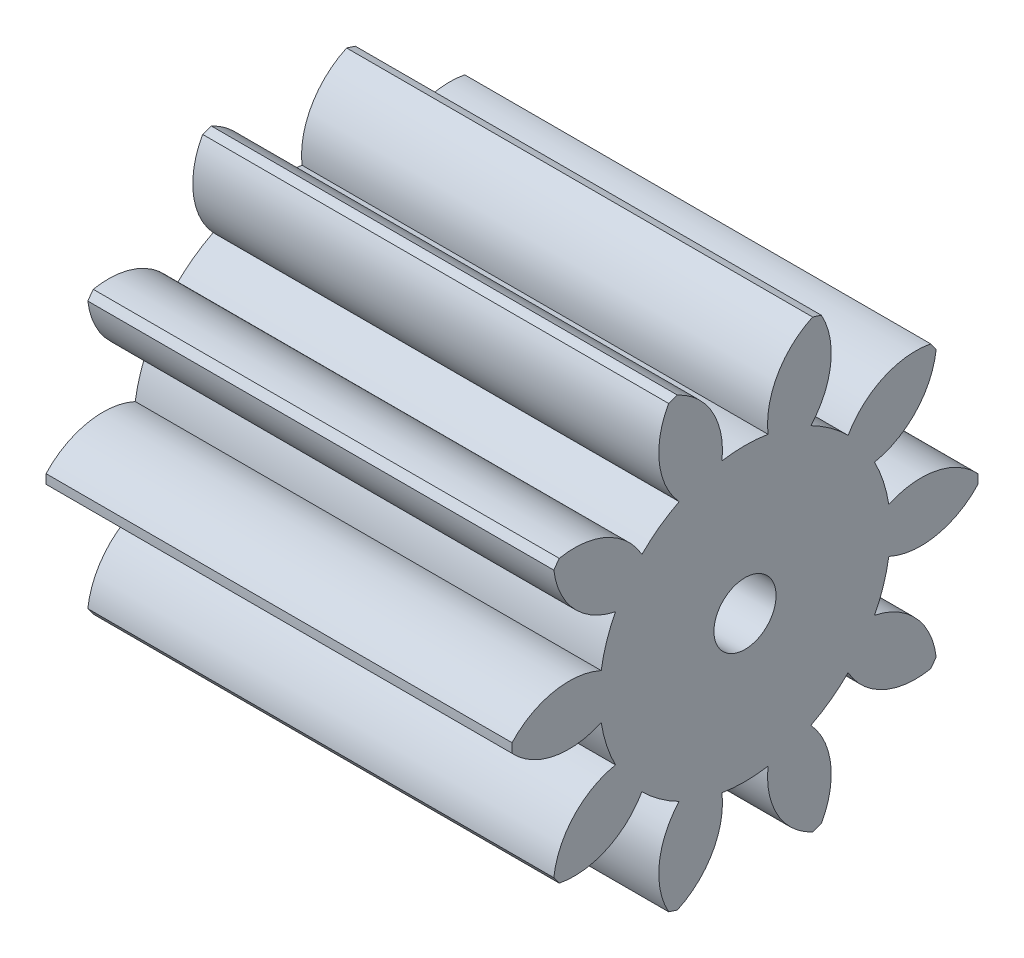
SolidWorks part; units mm, degrees
ref_plane "Plane1" through (0, 0, 0) normal (0, 0, 1) x (1, 0, 0)
ref_plane "Plane2" through (0, 0, 0) normal (0, 1, 0) x (1, 0, 0)
ref_plane "Plane3" through (0, 0, 0) normal (1, 0, 0) x (0, 0, -1)
other "Configuration Table"
sketch "HoldingSke" plane through (0, 0, 0) normal (0, 1, 0) x (1, 0, 0)
  line L0 (0, 0) -> (1.9696, -0.3473)
  line L1 (-15, 0) -> (100, 0) construction
  line L2 (0, 0) -> (-2.1039, 2.3779)
  line L3 (0, 0) -> (-11.863, 4.5341)
  line L4 (0, 0) -> (8.5048, 1.4996)
  line L5 (0, 0) -> (-46.8476, -17.4728)
  line L6 (0, 0) -> (-4.9738, -3.3558)
  line L7 (-2.1039, 2.3779) -> (8.6586, 51.2059)
  line L8 (-76.2, 54.61) -> (-76.1, 54.61)
  line L9 (-71.009, 38.7566) -> (-53.1078, 45.2721)
  line L10 (-76.2, 71.12) -> (104.1128, 71.12)
  line L11 (0, 0) -> (-6, 0)
  line L12 (-76.2, 101.6) -> (-76.181, 101.6)
  line L13 (24.9733, 27.94) -> (52.9518, 28.4284)
  line L14 (24.9733, 27.94) -> (24.9743, 27.94)
  line L15 (24.9733, 27.94) -> (100.4006, 29.5858)
  line L16 (-63.627, -0.5) -> (-12.827, -0.5)
  circle A0 centre (0, 0) radius 0.4
  circle A1 centre (0, 0) radius 1.874
  circle A2 centre (0, 0) radius 37.5
  circle A3 centre (0, 0) radius 0.4
  dimension "MHD" = 3.748
  dimension "Hub_dia" = 75
  dimension "Bore" = 0.8
  dimension "MBD" = 0.8
  dimension "Num_teeth" = 10
  dimension "Pitch" = 2
  dimension "Overall_len" = 50
  dimension "Show_teeth" = 10
  dimension "Thickness" = 6
  dimension "OAL" = 50.0001
  dimension "T_dim" = 0.1
  dimension "Ap" = 20
  dimension "H" = 19.05
  dimension "Pitch_radius" = 180.3128
  dimension "Width" = 6
  dimension "Backlash" = 0.019
  dimension "Addendum_fac" = 1
  dimension "Dedendum_fac" = 1.25
  dimension "Clearance_fac" = 0.25
  dimension "Dedendum_add" = 0.001
  dimension "Module" = 0.5
sketch "BasProSke" plane through (0, 0, 0) normal (0, 1, 0) x (1, 0, 0)
  line L0 (-10, 0) -> (60, 0) construction
  line L1 (0, 0) -> (0, 3)
  line L2 (0, 0) -> (6, 0)
  line L3 (6, 0) -> (6, 3)
  line L4 (6, 3) -> (0, 3)
  dimension "Thickness" = 6
  dimension "Diameter" = 6
revolve "Base-Revolve" add sketch "BasProSke" angle 360 about L0
sketch "TooCutSke" plane through (0, 0, 0) normal (1, 0, 0) x (0, 0, -1)
  line L1 (0, 0) -> (0, 107) construction
  line L2 (0, 0) -> (-0.4243, 2.4637) construction
  line L3 (0, 0) -> (-1.5292, 4.7063) construction
  line L4 (-0.4243, 2.4637) -> (-0.7646, 2.3532) construction
  arc A0 (0.2964, 1.8504) -> (-0.2964, 1.8504) centre (0, 0) ccw
  arc A1 (0.9059, 2.8866) -> (-0.9059, 2.8866) centre (0, 0) ccw
  circle A2 centre (0, 0) radius 2.5 construction
  circle A3 centre (0, 0) radius 2.3492 construction
  arc A4 (-0.2964, 1.8504) -> (-0.9059, 2.8866) centre (-1.2901, 1.9633) ccw
  arc A5 (0.9059, 2.8866) -> (0.2964, 1.8504) centre (1.2901, 1.9633) ccw
  dimension "Root_dia" = 3.748
  dimension "Overcut_dia" = 6.0508
  dimension "Pitch_dia" = 5
  dimension "Base_dia" = 4.6985
  dimension "Flank_rad" = 1
  dimension "Half_ang" = 18
  dimension "Half_CT" = 0.3578
extrude "ToothCut" cut sketch "TooCutSke" along normal through all
fillet "Breaks" [suppressed] radius 0.01
fillet "RootFillets" [suppressed] radius 0.126
pattern_circular "TeethCuts" count 10 every 36 about axis through (-10, 0, 0) along (1, 0, 0) of "ToothCut", "RootFillets", "Breaks"
sketch "HubNeaOneSke" plane through (0, 0, 0) normal (-1, 0, 0) x (0, 0, 1)
  circle A0 centre (0, 0) radius 1.874
  dimension "Diameter" = 3.748
extrude "HubNearOne" [suppressed] add sketch "HubNeaOneSke" along normal blind 44.0001
sketch "HubNeaBotSke" plane through (0, 0, 0) normal (-1, 0, 0) x (0, 0, 1)
  circle A0 centre (0, 0) radius 1.874
  dimension "Diameter" = 3.748
extrude "HubNearBoth" [suppressed] add sketch "HubNeaBotSke" along normal blind 22
ref_plane "FarPln" through (6, 0, 0) normal (1, 0, 0) x (0, 0, -1)
sketch "HubFarSke" plane through (6, 0, 0) normal (1, 0, 0) x (0, 0, -1)
  circle A0 centre (0, 0) radius 1.874
  dimension "Diameter" = 3.748
extrude "HubFar" [suppressed] add sketch "HubFarSke" along normal blind 22
sketch "BorSke" plane through (0, 0, 0) normal (1, 0, 0) x (0, 0, -1)
  circle A0 centre (0, 0) radius 0.4
  dimension "Diameter" = 0.8
extrude "Bore" cut sketch "BorSke" along normal mid plane 100.0001
sketch "KeySke" plane through (0, 0, 0) normal (1, 0, 0) x (0, 0, -1)
  line L0 (-0.05, 0) -> (-0.05, 0.5)
  line L1 (-0.05, 0.5) -> (0.05, 0.5)
  line L2 (0.05, 0.5) -> (0.05, 0)
  line L3 (0, 0) -> (0, 34) construction
  line L4 (-0.05, 0) -> (0.05, 0)
  dimension "Offset" = 0.5
  dimension "Width" = 0.1
extrude "Keyway" [suppressed] cut sketch "KeySke" along normal mid plane 100.0001
pattern_circular "Keyway2" [suppressed] count 2 every 90 about axis through (-10, 0, 0) along (1, 0, 0)
equation "' \"Module@HoldingSke\" = 6.35"
equation "' \"Num_teeth@HoldingSke\" = 12"
equation "' \"Ap@HoldingSke\" =  20"
equation "' \"Ap@HoldingSke\" = 20"
equation "' \"Width@HoldingSke\" = 0.5 * 25.4"
equation "' \"Hub_dia@HoldingSke\"= 1 * 25.4"
equation "' \"Hub_dia@HoldingSke\" = 1 * 25.4"
equation "' \"Overall_len@HoldingSke\" = 1.0 * 25.4"
equation "' \"Bore@HoldingSke\" = 0.75 * 25.4"
equation "' \"T_dim@HoldingSke\" = 0.1 * 25.4"
equation "' \"Width@KeySke\" = 0.25 * 25.4"
equation "' \"Show_teeth@HoldingSke\" = 13"
equation "' \"Backlash@HoldingSke\" = 0.009 * 25.4"
equation "' \"Addendum_fac@HoldingSke\" = 1.0"
equation "' \"Dedendum_fac@HoldingSke\" = 1.25"
equation "' \"Dedendum_add@HoldingSke\" = 0.00005 * 25.4"
equation "' \"Clearance_fac@HoldingSke\" = 0.25"
equation "\"Pitch@HoldingSke\" = 1 / \"Module@HoldingSke\""
equation "\"Overcut_dia@TooCutSke\" = (\"Num_teeth@HoldingSke\" + 2 * \"Addendum_fac@HoldingSke\") / \"Pitch@HoldingSke\" + 0.002 * 25.4"
equation "\"Pitch_dia@TooCutSke\" = \"Num_teeth@HoldingSke\" / \"Pitch@HoldingSke\""
equation "\"Base_dia@TooCutSke\" = \"Num_teeth@HoldingSke\" / \"Pitch@HoldingSke\" * cos((\"Ap@HoldingSke\"  * 3.14159265 / 180))"
equation "\"Root_dia@TooCutSke\" = (\"Num_teeth@HoldingSke\" + 2) / \"Pitch@HoldingSke\" - 2 * (\"Addendum_fac@HoldingSke\" + \"Dedendum_fac@HoldingSke\") / \"Pitch@HoldingSke\" - \"Dedendum_add@HoldingSke\" * 2"
equation "\"Half_ang@TooCutSke\" = 180 / \"Num_teeth@HoldingSke\""
equation "\"Half_CT@TooCutSke\" = \"Num_teeth@HoldingSke\" / \"Pitch@HoldingSke\" * sin((3.14159265 / 2 / \"Num_teeth@HoldingSke\")) / 2 - 7 * \"Backlash@HoldingSke\" / 4"
equation "\"Flank_rad@TooCutSke\" = \"Num_teeth@HoldingSke\" / \"Pitch@HoldingSke\" / 5"
equation "\"Radius@RootFillets\" = \"Clearance_fac@HoldingSke\" / \"Pitch@HoldingSke\" + \"Dedendum_add@HoldingSke\""
equation "\"Break_rad@Breaks\" = 0.02 / \"Pitch@HoldingSke\""
equation "\"Thickness@HoldingSke\" = \"Width@HoldingSke\""
equation "\"OAL@HoldingSke\" = \"Thickness@HoldingSke\""
equation "\"MHD@HoldingSke\" = (\"Num_teeth@HoldingSke\" + 2) / \"Pitch@HoldingSke\" - 2 * (\"Addendum_fac@HoldingSke\" + \"Dedendum_fac@HoldingSke\")  / \"Pitch@HoldingSke\" - \"Dedendum_add@HoldingSke\" * 2"
equation "\"MBD@HoldingSke\" = (\"Num_teeth@HoldingSke\" + 2) / \"Pitch@HoldingSke\" - 2 * (\"Addendum_fac@HoldingSke\" + \"Dedendum_fac@HoldingSke\")  / \"Pitch@HoldingSke\" - \"Dedendum_add@HoldingSke\" * 2 - 0.002 * 25.4"
equation "\"MHD@HoldingSke\" = ((sgn( \"MHD@HoldingSke\" - \"Hub_dia@HoldingSke\" )-1)*( \"MHD@HoldingSke\" - \"Hub_dia@HoldingSke\" ))/-2+ \"Hub_dia@HoldingSke\""
equation "\"MBD@HoldingSke\" = ((sgn( \"MBD@HoldingSke\" - \"Bore@HoldingSke\" )-1)*( \"MBD@HoldingSke\" - \"Bore@HoldingSke\" ))/-2+ \"Bore@HoldingSke\""
equation "\"OAL@HoldingSke\" = ((sgn( \"OAL@HoldingSke\" - \"Overall_len@HoldingSke\" )+1)*( \"OAL@HoldingSke\" - \"Overall_len@HoldingSke\" ))/2 + \"Overall_len@HoldingSke\" + 0.000002 * 25.4"
equation "\"Num_teeth@TeethCuts\" = int( \"Show_teeth@HoldingSke\" ) + 1"
equation "\"Num_teeth@TeethCuts\" = ((sgn( \"Num_teeth@TeethCuts\" - \"Num_teeth@HoldingSke\" )-1)*( \"Num_teeth@TeethCuts\" - \"Num_teeth@HoldingSke\" ))/-2+ \"Num_teeth@HoldingSke\""
equation "\"Num_teeth@TeethCuts\" = ((sgn( \"Num_teeth@TeethCuts\" - 2.0)+1)*( \"Num_teeth@TeethCuts\" - 2.0))/2 +2.0"
equation "\"Angle@TeethCuts\" = 360.0 / \"Num_teeth@HoldingSke\""
equation "\"Diameter@BasProSke\" = (\"Num_teeth@HoldingSke\" + 2 * \"Addendum_fac@HoldingSke\") / \"Pitch@HoldingSke\""
equation "\"Thickness@BasProSke\"  = \"Thickness@HoldingSke\""
equation "' \"Fillet_rad@BasProSke\" =  \"Thickness@HoldingSke\" * 0.05"
equation "' \"Fillet_rad@BasProSke\" = \"Thickness@HoldingSke\" * 0.05"
equation "\"MHD@HoldingSke\" = ((sgn( \"MHD@HoldingSke\" - \"Root_dia@TooCutSke\" )-1)*( \"MHD@HoldingSke\" - \"Root_dia@TooCutSke\" ))/-2+ \"Root_dia@TooCutSke\""
equation "\"Diameter@HubNeaOneSke\" = \"MHD@HoldingSke\""
equation "\"Length@HubNearOne\" = \"OAL@HoldingSke\" - \"Thickness@BasProSke\""
equation "\"Diameter@HubNeaBotSke\" = \"MHD@HoldingSke\""
equation "\"Length@HubNearBoth\" = ( \"OAL@HoldingSke\" - \"Thickness@BasProSke\" ) / 2.0"
equation "\"Thickness@FarPln\" = \"Thickness@BasProSke\""
equation "\"Diameter@HubFarSke\" = \"MHD@HoldingSke\""
equation "\"Length@HubFar\" = ( \"OAL@HoldingSke\" - \"Thickness@BasProSke\" ) / 2.0"
equation "\"Diameter@BorSke\" = \"MBD@HoldingSke\""
equation "\"D1@Bore\" = \"OAL@HoldingSke\" * 2.0"
equation "\"D1@Keyway\" = \"OAL@HoldingSke\" * 2.0"
equation "\"Offset@KeySke\" = \"T_dim@HoldingSke\" + \"MBD@HoldingSke\" / 2.0"
